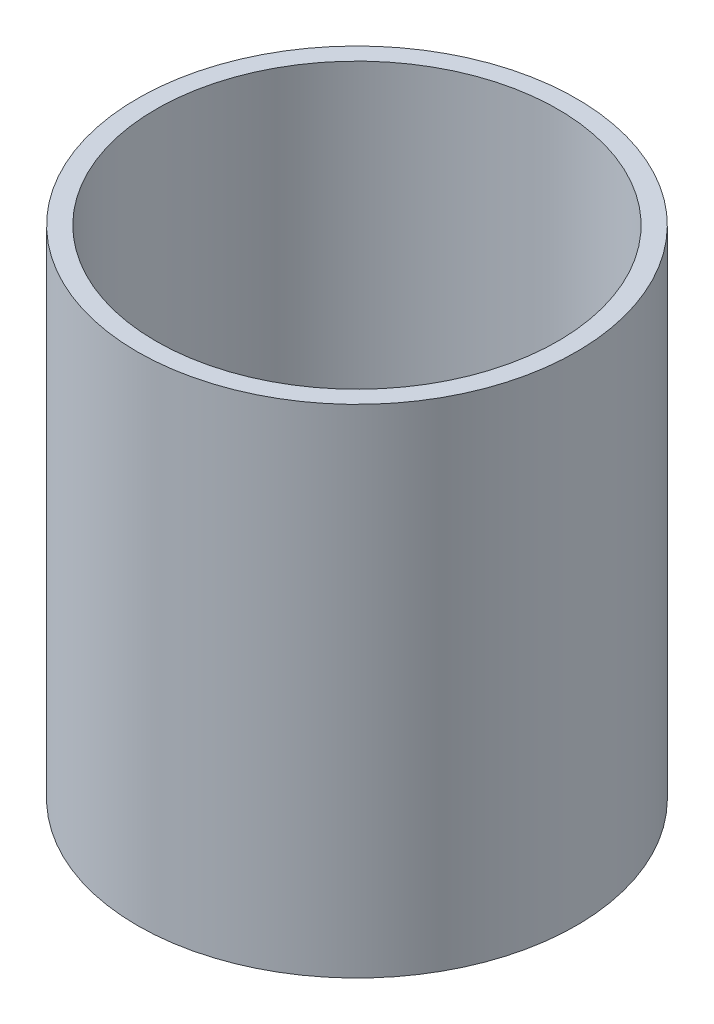
SolidWorks part; units mm, degrees
ref_plane "Front Plane" through (0, 0, 0) normal (0, 0, 1) x (1, 0, 0)
ref_plane "Top Plane" through (0, 0, 0) normal (0, 1, 0) x (1, 0, 0)
ref_plane "Right Plane" through (0, 0, 0) normal (1, 0, 0) x (0, 0, -1)
other "Configuration Table"
sketch "Sketch1" plane through (0, 0, 0) normal (0, 1, 0) x (1, 0, 0)
  circle A0 centre (0, 0) radius 84.15
  circle A1 centre (0, 0) radius 77.05
extrude "Boss-Extrude1" add sketch "Sketch1" along normal blind 190.5
